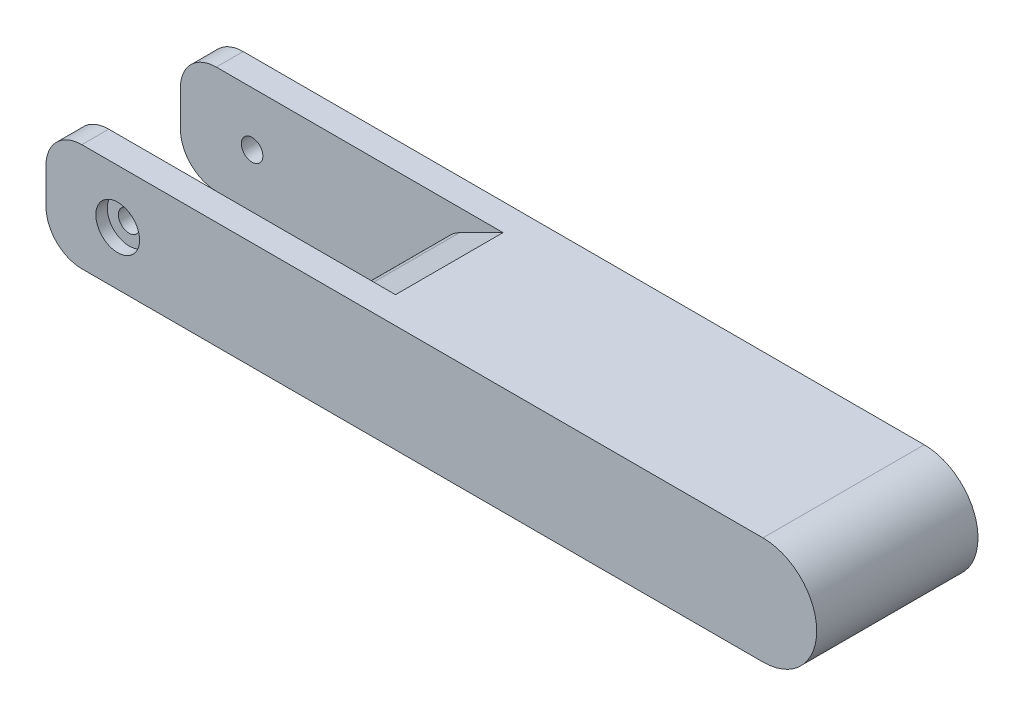
SolidWorks part; units mm, degrees
material "3.0205 (EN-AW 1200)"
ref_plane "Front Plane" through (0, 0, 0) normal (0, 0, 1) x (1, 0, 0)
ref_plane "Top Plane" through (0, 0, 0) normal (0, 1, 0) x (1, 0, 0)
ref_plane "Right Plane" through (0, 0, 0) normal (1, 0, 0) x (0, 0, -1)
sketch "Sketch1" plane through (0, 0, 0) normal (0, 0, 1) x (1, 0, 0)
  line L1 (-100, -15) -> (100, -15)
  line L2 (-100, -15) -> (-100, 15)
  line L3 (-100, 15) -> (100, 15)
  line L5 (0, 15) -> (0, -15) construction
  line L6 (-100, 0) -> (100, 0) construction
  circle A0 centre (-80, 0) radius 3
  arc A1 (100, -15) -> (100, 15) centre (100, 0) ccw
  point P0 (0, 0)
  dimension "D2" = 6
  dimension "D1" = 180
  dimension "D3" = 30
  dimension "D4" = 20
extrude "Boss-Extrude1" add sketch "Sketch1" along normal mid plane 45
sketch "Sketch3" plane through (0, 15, 0) normal (0, 1, 0) x (1, 0, 0)
  line L0 (-100, -22.5) -> (-100, 22.5) construction
  line L1 (-100, -15) -> (-40, -15)
  line L3 (-100, 15) -> (-40, 15)
  line L4 (-40, -15) -> (-40, 15)
  line L5 (-100, 15) -> (-100, -15) construction
  line L6 (-100, 0) -> (-40, 0) construction
  line L7 (-100, 15) -> (-100, -15)
  point P0 (-100, 0)
  dimension "D1" = 60
  dimension "D2" = 30
extrude "Cut-Extrude1" cut sketch "Sketch3" against normal through all
fillet "Fillet1" radius 10 4 edges at (-100, -15, 18.75) (-100, -15, -18.75) (-100, 15, 18.75) (-100, 15, -18.75)
sketch "Sketch4" plane through (0, 0, -15) normal (0, 0, -1) x (-1, 0, 0)
  line L0 (40, 15) -> (40, 0)
  line L1 (-100, 15) -> (90, 15) construction
  line L2 (40, 0) -> (10, 15)
  line L3 (10, 15) -> (40, 15)
  line L4 (100, 5) -> (100, -5) construction
  dimension "D1" = 60
  dimension "D2" = 30
sketch "Sketch5" plane through (0, 0, -15) normal (0, 0, -1) x (-1, 0, 0)
  line L0 (40, 0) -> (40, -15)
  line L1 (40, -15) -> (10, -15)
  line L2 (90, -15) -> (-100, -15) construction
  line L3 (10, -15) -> (40, 0)
  dimension "D1" = 30
extrude "Cut-Extrude2" cut sketch "Sketch4" against normal blind 30 contours L3 L0 L2
extrude "Cut-Extrude4" cut sketch "Sketch5" against normal blind 30 contours L0 L1 L3
fillet "Fillet2" radius 10 1 edges at (-40, 0, 0)
sketch "Sketch6" plane through (0, 0, 22.5) normal (0, 0, 1) x (1, 0, 0)
  circle A0 centre (-80, 0) radius 6.1
  dimension "D1" = 12.2
extrude "Cut-Extrude5" cut sketch "Sketch6" against normal blind 3.2
sketch "Sketch7" plane through (0, 0, -22.5) normal (0, 0, -1) x (-1, 0, 0)
  circle A0 centre (80, 0) radius 6.1
  dimension "D1" = 12.2
extrude "Cut-Extrude6" cut sketch "Sketch7" against normal blind 3.2
equation "\"link_thickness\" = 50"
equation "\"cut_depth\" = 30"
equation "\"cut_width\" = 30"
equation "\"thigh_cut_depth\" = 80"
equation "\"foot_cut_depth\" = 60"
equation "\"D1@Sketch3\"=\"foot_cut_depth\""
equation "\"D1@Sketch4\"=\"foot_cut_depth\""
equation "\"D2@Sketch4\"=\"cut_depth\""
equation "\"D1@Sketch5\"=\"cut_depth\""
equation "\"D1@Cut-Extrude2\"=\"foot_cut_width\""
equation "\"D1@Cut-Extrude4\"=\"foot_cut_width\""
equation "\"link_length\" = 180"
equation "\"D1@Sketch1\"=\"link_length\""
equation "\"foot_cut_width\" = 30"
equation "\"D2@Sketch3\"=\"foot_cut_width\""
